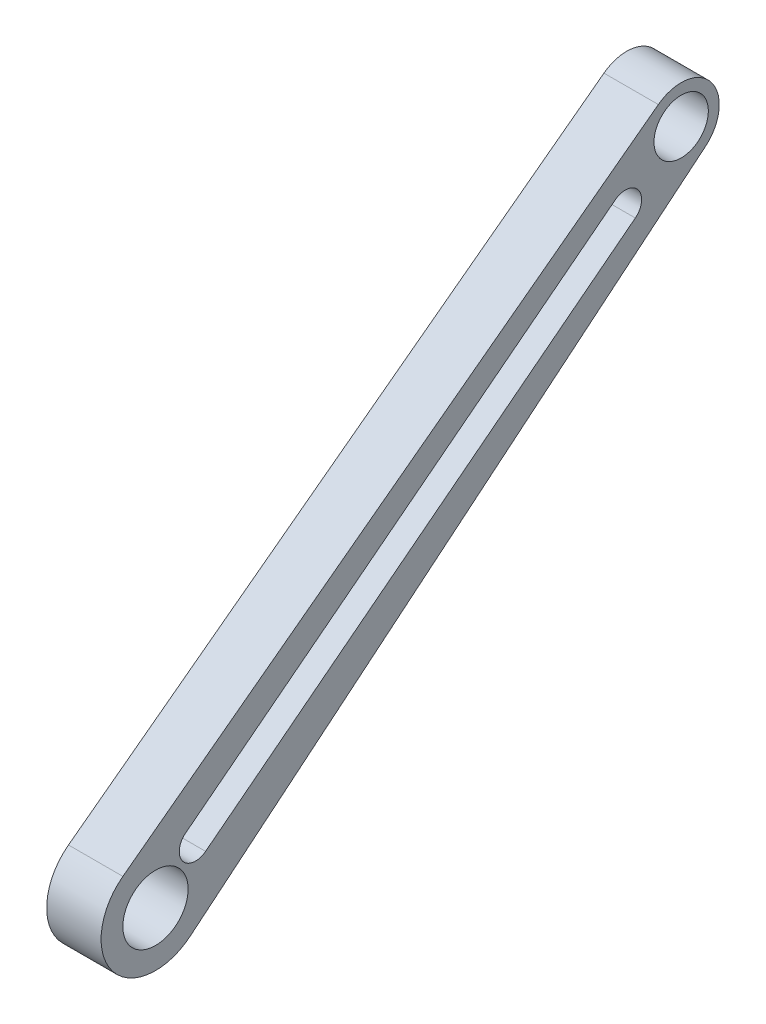
SolidWorks part; units mm, degrees
ref_plane "Ön Düzlem" through (0, 0, 0) normal (0, 0, 1) x (1, 0, 0)
ref_plane "Üst Düzlem" through (0, 0, 0) normal (0, 1, 0) x (1, 0, 0)
ref_plane "Sağ Düzlem" through (0, 0, 0) normal (1, 0, 0) x (0, 0, -1)
sketch "Çizim1" plane through (0, 0, 0) normal (1, 0, 0) x (0, 0, -1)
  line L0 (-29.9574, 40.0319) -> (462.1641, 408.3056)
  line L1 (31.8745, -38.523) -> (505.4465, 353.3172)
  line L2 (36.8434, 33.8018) -> (431.7911, 340.4226) construction
  line L3 (27.6448, 45.6502) -> (422.5925, 352.271)
  line L4 (46.042, 21.9534) -> (440.9898, 328.5742)
  arc A0 (-29.9574, 40.0319) -> (31.8745, -38.523) centre (0, 0) ccw
  arc A1 (505.4465, 353.3172) -> (462.1641, 408.3056) centre (483.1343, 380.2833) ccw
  circle A2 centre (0, 0) radius 30
  circle A3 centre (483.1343, 380.2833) radius 25
  arc A4 (27.6448, 45.6502) -> (46.042, 21.9534) centre (36.8434, 33.8018) ccw
  arc A5 (440.9898, 328.5742) -> (422.5925, 352.271) centre (431.7911, 340.4226) ccw
  point P11 (234.3173, 187.1122)
  point P16 (443.6396, 349.6212)
  dimension "D1" = 100
  dimension "D2" = 70
  dimension "D3" = 60
  dimension "D4" = 50
  dimension "D7" = 50
  dimension "D5" = 500
  dimension "D6" = 50
  dimension "D8" = 30
extrude "Yükseklik-Ekstrüzyon1" add sketch "Çizim1" along normal blind 50
